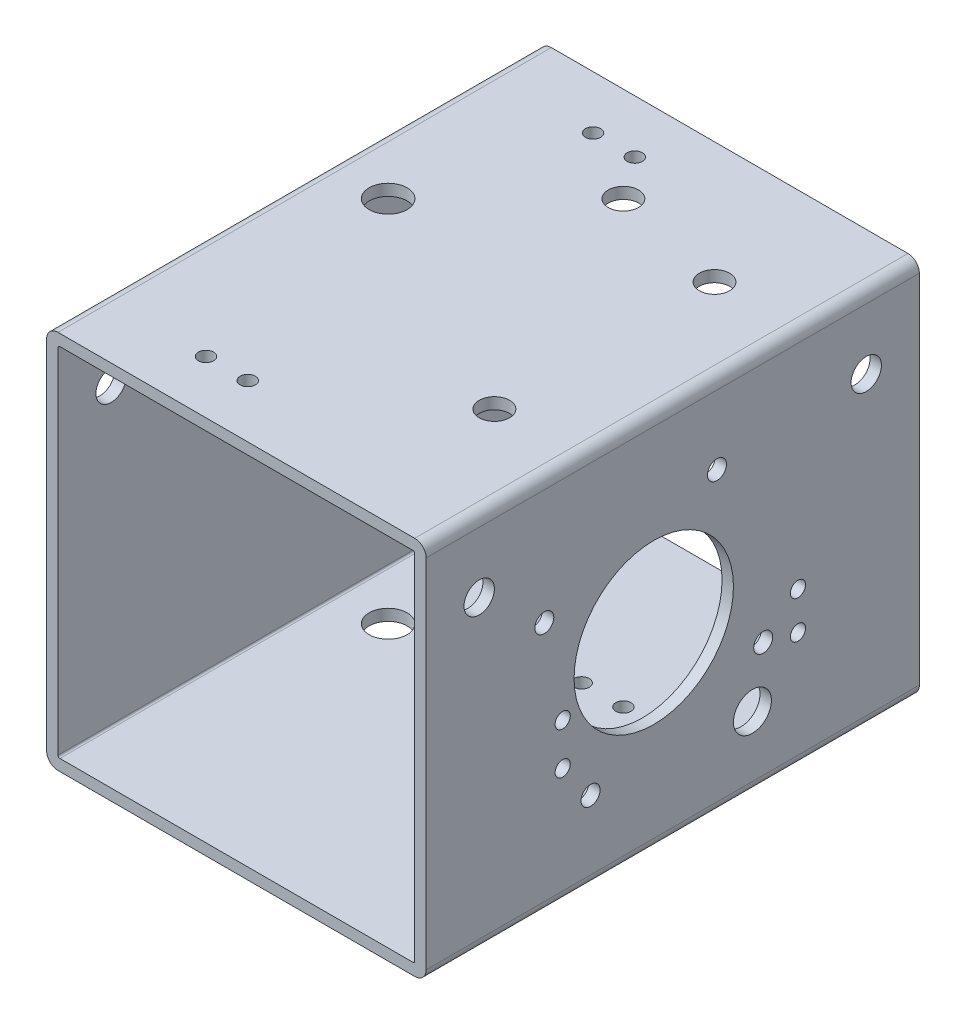
SolidWorks part; units mm, degrees
ref_plane "Front Plane" through (0, 0, 0) normal (0, 0, 1) x (1, 0, 0)
ref_plane "Top Plane" through (0, 0, 0) normal (0, 1, 0) x (1, 0, 0)
ref_plane "Right Plane" through (0, 0, 0) normal (1, 0, 0) x (0, 0, -1)
sketch "Sketch1" plane through (0, 0, 0) normal (0, 0, 1) x (1, 0, 0)
  line L1 (-50, 50) -> (50, 50)
  line L2 (-50, 50) -> (-50, -50)
  line L3 (-50, -50) -> (50, -50)
  line L4 (50, 50) -> (50, -50)
  line L5 (-50, 50) -> (50, -50) construction
  line L6 (-50, -50) -> (50, 50) construction
  point P0 (0, 0)
  dimension "D1" = 100
  dimension "D2" = 100
extrude "Extrude-Thin1" add sketch "Sketch1" along normal blind 130 thin
fillet "Fillet1" radius 0.5 4 edges at (-47, -47, 65) (-47, 47, 65) (47, 47, 65) (47, -47, 65)
fillet "Fillet2" radius 3 4 edges at (50, -50, 65) (-50, -50, 65) (50, 50, 65) (-50, 50, 65)
sketch "Holes - top" plane through (0, 0, 0) normal (0, 1, 0) x (1, 0, 0)
  line L0 (-3, 0) -> (-3, -130) construction
  line L1 (47, -130) -> (-47, -130) construction
  line L2 (-23, 0) -> (-23, -130) construction
  line L3 (47, 0) -> (-47, 0) construction
  line L4 (17, 0) -> (17, -130) construction
  circle A0 centre (-34, -56) radius 11 construction
  circle A1 centre (28, -90) radius 11 construction
  circle A2 centre (28, -32) radius 11 construction
  dimension "D4" = 22
  dimension "D1" = 40
  dimension "D2" = 40
  dimension "D3" = 32
  dimension "D5" = 56
  dimension "D6" = 3
hole_wizard "Ø8.0 (8) Diameter Hole2" positions "Sketch6" profile "Sketch5" hole size "Ø8.0" standard "ANSI Metric" end condition through all
sketch "Sketch6" plane through (0, 50, 0) normal (0, 1, 0) x (1, 0, 0)
  point P0 (28, -32)
  point P6 (28, -90)
sketch "Sketch5" plane through (28, 50, 32) normal (1, 0, 0) x (0, 0, 1)
  line L0 (0, 0) -> (0, 100)
  line L1 (0, 100) -> (4, 100)
  line L2 (4, 100) -> (4, 0)
  line L5 (4, 0) -> (0, 0)
  line L11 (0, -6.35) -> (0, 107.95) construction
  dimension "Thru Hole Dia." = 8
  dimension "Thru Hole Depth" = 100
sketch "Holes - side" plane through (0, 0, 0) normal (1, 0, 0) x (0, 0, -1)
  line L0 (0, 0) -> (-130, 0) construction
  line L1 (-130, -47) -> (-130, 47) construction
  line L2 (-130, 20) -> (0, 20) construction
  line L3 (0, -47) -> (0, 47) construction
  line L4 (-130, -20) -> (0, -20) construction
  circle A0 centre (-116, 31) radius 11 construction
  circle A1 centre (-14, 31) radius 11 construction
  circle A2 centre (-44, -31) radius 11 construction
  dimension "D1" = 40
  dimension "D2" = 22
  dimension "D3" = 14
  dimension "D4" = 14
  dimension "D5" = 44
hole_wizard "Ø8.0 (8) Diameter Hole3" positions "Sketch9" profile "Sketch8" hole size "Ø8.0" standard "ANSI Metric" end condition through all
sketch "Sketch9" plane through (50, 0, 0) normal (1, 0, 0) x (0, 0, -1)
  point P0 (-14, 31)
  point P3 (-116, 31)
sketch "Sketch8" plane through (50, 31, 14) normal (0, 1, 0) x (0, 0, -1)
  line L0 (0, 0) -> (0, 100)
  line L1 (0, 100) -> (4, 100)
  line L2 (4, 100) -> (4, 0)
  line L5 (4, 0) -> (0, 0)
  line L11 (0, -6.35) -> (0, 107.95) construction
  dimension "Thru Hole Dia." = 8
  dimension "Thru Hole Depth" = 100
hole_wizard "Ø10.0 (10) Diameter Hole1" positions "Sketch12" profile "Sketch11" hole size "Ø10.0" standard "ANSI Metric" end condition through all
sketch "Sketch12" plane through (0, 50, 0) normal (0, 1, 0) x (1, 0, 0)
  point P0 (-34, -56)
sketch "Sketch11" plane through (-34, 50, 56) normal (1, 0, 0) x (0, 0, 1)
  line L0 (0, 0) -> (0, 100)
  line L1 (0, 100) -> (5, 100)
  line L2 (5, 100) -> (5, 0)
  line L5 (5, 0) -> (0, 0)
  line L11 (0, -6.35) -> (0, 107.95) construction
  dimension "Thru Hole Dia." = 10
  dimension "Thru Hole Depth" = 100
hole_wizard "Ø10.0 (10) Diameter Hole2" positions "Sketch14" profile "Sketch13" hole size "Ø10.0" standard "ANSI Metric" end condition through all
sketch "Sketch14" plane through (50, 0, 0) normal (1, 0, 0) x (0, 0, -1)
  point P0 (-44, -31)
sketch "Sketch13" plane through (50, -31, 44) normal (0, 1, 0) x (0, 0, -1)
  line L0 (0, 0) -> (0, 100)
  line L1 (0, 100) -> (5, 100)
  line L2 (5, 100) -> (5, 0)
  line L5 (5, 0) -> (0, 0)
  line L11 (0, -6.35) -> (0, 107.95) construction
  dimension "Thru Hole Dia." = 10
  dimension "Thru Hole Depth" = 100
sketch "Holes - Nema 23 motor" plane through (0, 0, 0) normal (1, 0, 0) x (0, 0, -1)
  line L0 (-98.8427, 16.6524) -> (-53.3476, 28.8427) construction
  line L1 (-98.8427, 16.6524) -> (-86.6524, -28.8427) construction
  line L2 (-53.3476, 28.8427) -> (-41.1573, -16.6524) construction
  line L3 (-86.6524, -28.8427) -> (-41.1573, -16.6524) construction
  line L4 (-98.8427, 16.6524) -> (-41.1573, -16.6524) construction
  line L5 (-53.3476, 28.8427) -> (-86.6524, -28.8427) construction
  line L6 (0, 0) -> (-130, 0) construction
  point P1 (-70, 0)
  dimension "D1" = 70
  dimension "D2" = 47.1
  dimension "D3" = 47.1
  dimension "D4" = 15
hole_wizard "Ø21.0 (21) Diameter Hole1" positions "Sketch24" profile "Sketch23" hole size "Ø21.0" standard "ANSI Metric"
sketch "Sketch24" plane through (50, 0, 0) normal (1, 0, 0) x (0, 0, -1)
  point P0 (-70, 0)
sketch "Sketch23" plane through (50, 0, 70) normal (0, 1, 0) x (0, 0, -1)
  line L0 (0, 0) -> (0, 3)
  line L1 (0, 3) -> (21, 3)
  line L2 (21, 3) -> (21, 0)
  line L5 (21, 0) -> (0, 0)
  line L11 (0, -6.35) -> (0, 107.95) construction
  dimension "Thru Hole Dia." = 42
  dimension "Thru Hole Depth" = 3
hole_wizard "Ø5.0 (5) Diameter Hole1" positions "Sketch26" profile "Sketch25" hole size "Ø5.0" standard "ANSI Metric"
sketch "Sketch26" plane through (50, 0, 0) normal (1, 0, 0) x (0, 0, -1)
  point P0 (-41.1573, -16.6524)
  point P3 (-53.3476, 28.8427)
  point P6 (-98.8427, 16.6524)
  point P9 (-86.6524, -28.8427)
sketch "Sketch25" plane through (50, -16.6524, 41.1573) normal (0, 1, 0) x (0, 0, -1)
  line L0 (0, 0) -> (0, 3)
  line L1 (0, 3) -> (2.5, 3)
  line L2 (2.5, 3) -> (2.5, 0)
  line L5 (2.5, 0) -> (0, 0)
  line L11 (0, -6.35) -> (0, 107.95) construction
  dimension "Thru Hole Dia." = 5
  dimension "Thru Hole Depth" = 3
hole_wizard "Ø8.0 (8) Diameter Hole5" positions "Sketch32" profile "Sketch33" hole size "Ø8.0" standard "ANSI Metric"
sketch "Sketch32" plane through (0, 50, 0) normal (0, 1, 0) x (1, 0, 0)
  line L1 (47, 0) -> (-47, 0) construction
  line L2 (-50, -130) -> (-50, 0) construction
  point P0 (-3, -25)
  dimension "D1" = 47
  dimension "D2" = 25
sketch "Sketch33" plane through (-3, 50, 25) normal (1, 0, 0) x (0, 0, 1)
  line L0 (0, 0) -> (0, 3)
  line L1 (0, 3) -> (4, 3)
  line L2 (4, 3) -> (4, 0)
  line L5 (4, 0) -> (0, 0)
  line L11 (0, -6.35) -> (0, 107.95) construction
  dimension "Thru Hole Dia." = 8
  dimension "Thru Hole Depth" = 3
sketch "Sketch34" plane through (0, 50, 0) normal (0, 1, 0) x (1, 0, 0)
  line L0 (-50, -130) -> (-50, 0) construction
  line L1 (47, 0) -> (-47, 0) construction
  line L2 (-57.8798, -65) -> (-147.5435, -65) construction
  circle A0 centre (-22, -14) radius 2
  circle A1 centre (-11, -14) radius 2
  circle A2 centre (-11, -116) radius 2
  circle A3 centre (-22, -116) radius 2
  dimension "D1" = 4
  dimension "D2" = 28
  dimension "D3" = 14
  dimension "D4" = 11
  dimension "D5" = 65
extrude "Cut-Extrude1" cut sketch "Sketch34" against normal up to next
sketch "Sketch35" plane through (0, -50, 0) normal (0, -1, 0) x (1, 0, 0)
  line L0 (50, 130) -> (50, 0) construction
  line L1 (-47, 0) -> (47, 0) construction
  circle A0 centre (16, 44) radius 2
  circle A1 centre (5, 44) radius 2
  dimension "D1" = 4
  dimension "D2" = 34
  dimension "D3" = 44
  dimension "D4" = 11
extrude "Cut-Extrude2" cut sketch "Sketch35" against normal blind 10
sketch "Sketch36" plane through (-50, 0, 0) normal (-1, 0, 0) x (0, 0, 1)
  line L0 (0, 50) -> (130, 50) construction
  line L1 (0, 47) -> (0, -47) construction
  circle A0 centre (56, 19) radius 2
  circle A1 centre (56, 8) radius 2
  dimension "D1" = 4
  dimension "D2" = 31
  dimension "D3" = 56
  dimension "D4" = 11
extrude "Cut-Extrude3" cut sketch "Sketch36" against normal blind 10
sketch "Sketch37" plane through (50, 0, 0) normal (1, 0, 0) x (0, 0, -1)
  line L0 (0, -50) -> (-130, -50) construction
  line L1 (-130, -47) -> (-130, 47) construction
  circle A0 centre (-94, -19) radius 2
  circle A1 centre (-32, -19) radius 2
  circle A2 centre (-94, -8) radius 2
  circle A3 centre (-32, -9.0797) radius 2
  dimension "D1" = 31
  dimension "D2" = 4
  dimension "D3" = 36
  dimension "D4" = 11
  dimension "D5" = 98
extrude "Cut-Extrude4" cut sketch "Sketch37" against normal blind 10
sketch "Sketch38" plane through (-50, 0, 0) normal (-1, 0, 0) x (0, 0, 1)
  line L0 (0, 50) -> (130, 50) construction
  line L1 (0, 47) -> (0, -47) construction
  circle A0 centre (56, 35) radius 3.1
  circle A1 centre (56, -15) radius 3.1
  dimension "D1" = 15
  dimension "D2" = 65
  dimension "D3" = 56
  dimension "D4" = 6.2
extrude "Cut-Extrude5" cut sketch "Sketch38" against normal blind 10
sketch "Sketch39" plane through (0, -50, 0) normal (0, -1, 0) x (1, 0, 0)
  line L0 (-47, 0) -> (47, 0) construction
  line L1 (50, 130) -> (50, 0) construction
  circle A0 centre (-20, 44) radius 3.1
  circle A1 centre (35, 44) radius 3.1
  dimension "D1" = 6.2
  dimension "D2" = 44
  dimension "D3" = 15
  dimension "D4" = 70
extrude "Cut-Extrude6" cut sketch "Sketch39" against normal blind 10
equation "\"L\"= 130"
equation "\"D1@Extrude-Thin1\"=\"L\""
equation "\"d-bearing\"= 22'diameter of bearing"
equation "\"D4@Holes - top\"=\"d-bearing\""
equation "\"D2@Holes - side\"=\"d-bearing\""
